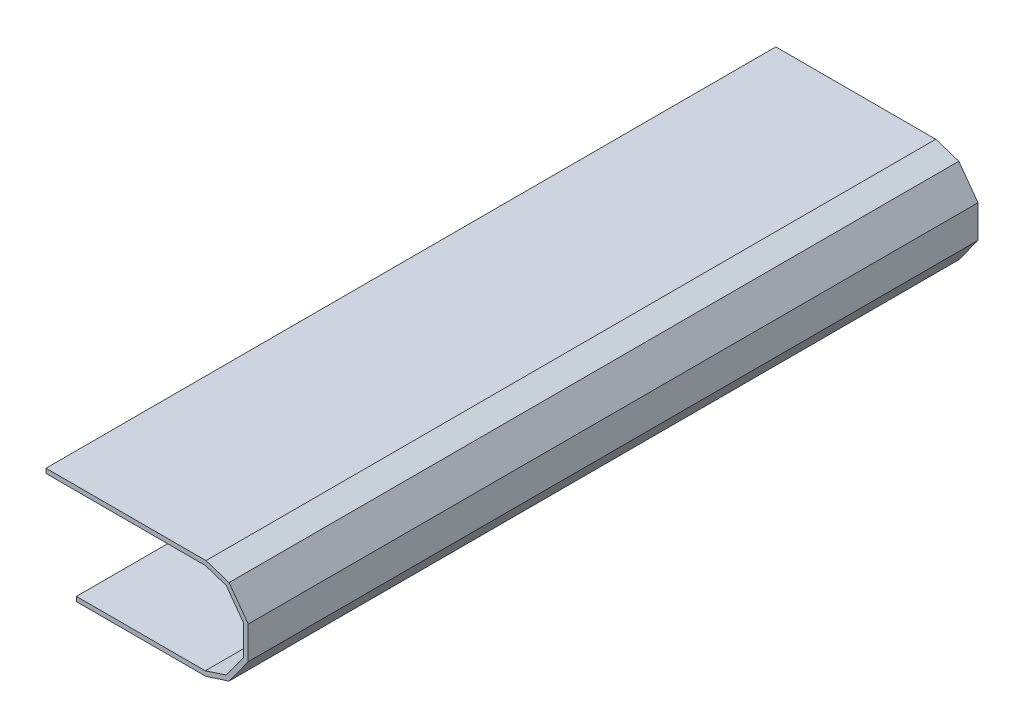
SolidWorks part; units mm, degrees
ref_plane "Plan de face" through (0, 0, 0) normal (0, 0, 1) x (1, 0, 0)
ref_plane "Plan de dessus" through (0, 0, 0) normal (0, 1, 0) x (1, 0, 0)
ref_plane "Plan de droite" through (0, 0, 0) normal (1, 0, 0) x (0, 0, -1)
sketch "Esquisse1" plane through (0, 0, 0) normal (0, 0, 1) x (1, 0, 0)
  line L0 (0, 30) -> (-80, 30)
  line L1 (-80, -33) -> (0, -33)
  line L2 (0, 30) -> (0, 0) construction
  line L3 (0, 31.5439) -> (-18.541, 25.5195) construction
  line L4 (-80, -30) -> (0, -30)
  line L5 (0, -33) -> (5.2267, -33)
  line L6 (-18.541, 25.5195) -> (-30, 9.7476) construction
  line L7 (-30, 9.7476) -> (-30, -9.7476) construction
  line L8 (0, 0) -> (-80, 0) construction
  line L9 (-30, -9.7476) -> (-18.541, -25.5195) construction
  line L10 (-18.541, -25.5195) -> (0, -31.5439) construction
  line L11 (4.7515, -30) -> (18.541, -25.5195)
  line L12 (18.541, -25.5195) -> (30, -9.7476)
  line L13 (30, -9.7476) -> (30, 9.7476)
  line L14 (-40, 30) -> (-40, -30) construction
  line L15 (30, 9.7476) -> (18.541, 25.5195)
  line L16 (-80, 30) -> (-80, -30) construction
  line L17 (18.541, 25.5195) -> (4.7515, 30)
  line L18 (0, 0) -> (0, -30) construction
  line L19 (0, 30) -> (0, 31.5439) construction
  line L20 (0, 30) -> (4.7515, 30)
  line L21 (5.2267, -33) -> (20.3951, -28.0715)
  line L22 (20.3951, -28.0715) -> (33, -10.7223)
  line L23 (33, -10.7223) -> (33, 10.7223)
  line L24 (0, -30) -> (4.7515, -30)
  line L25 (33, 10.7223) -> (20.3951, 28.0715)
  line L26 (4.7515, 30) -> (0, 31.5439) construction
  line L27 (20.3951, 28.0715) -> (5.2267, 33)
  line L28 (4.7515, -30) -> (0, -31.5439) construction
  line L29 (0, 33) -> (5.2267, 33)
  line L30 (0, 33) -> (-80, 33)
  line L31 (-80, 33) -> (-80, 30)
  line L32 (-80, -30) -> (-80, -33)
  circle A0 centre (0, 0) radius 30 construction
  point P3 (0, 30)
  dimension "D1" = 60
  dimension "D2" = 3
  dimension "D7" = 40
  dimension "D9" = 40
extrude "Boss.-Extru.1" add sketch "Esquisse1" along normal blind 480
sketch "Esquisse3" plane through (-80, 0, 0) normal (-1, 0, 0) x (0, 0, 1)
  line L1 (0, 30) -> (480, 30)
  line L2 (0, 30) -> (0, 33)
  line L3 (0, 33) -> (480, 33)
  line L4 (480, 30) -> (480, 33)
extrude "Boss.-Extru.2" add sketch "Esquisse3" along normal blind 20
